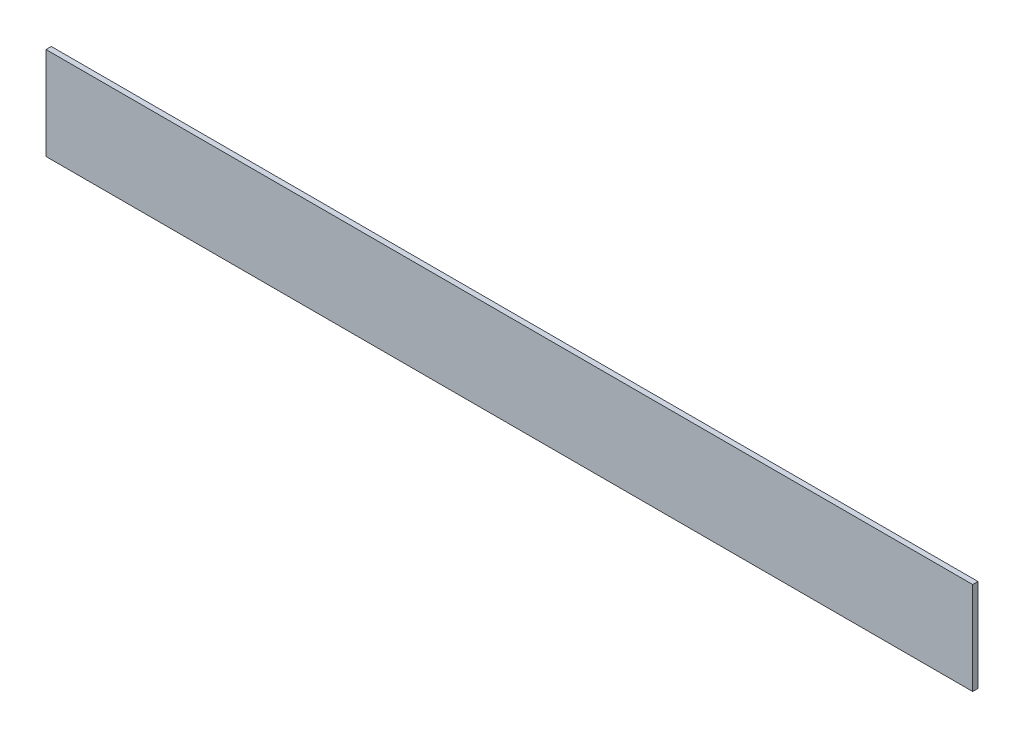
SolidWorks part; units mm, degrees
material "AISI 1020"
ref_plane "Front Plane" through (0, 0, 0) normal (0, 0, 1) x (1, 0, 0)
ref_plane "Top Plane" through (0, 0, 0) normal (0, 1, 0) x (1, 0, 0)
ref_plane "Right Plane" through (0, 0, 0) normal (1, 0, 0) x (0, 0, -1)
sketch "Sketch1" plane through (0, 0, 0) normal (0, 1, 0) x (1, 0, 0)
  line L9 (-211.2754, 25) -> (-211.2754, 23)
  line L10 (-211.2754, 23) -> (138.7246, 23)
  line L11 (-211.2754, 25) -> (138.7246, 25)
  line L12 (138.7246, 23) -> (138.7246, 25)
  point P4 (0, 0)
  point P10 (-36.2754, 25)
  point P16 (-36.2754, 25)
  dimension "D2" = 350
extrude "Boss-Extrude1" add sketch "Sketch1" along normal blind 35
